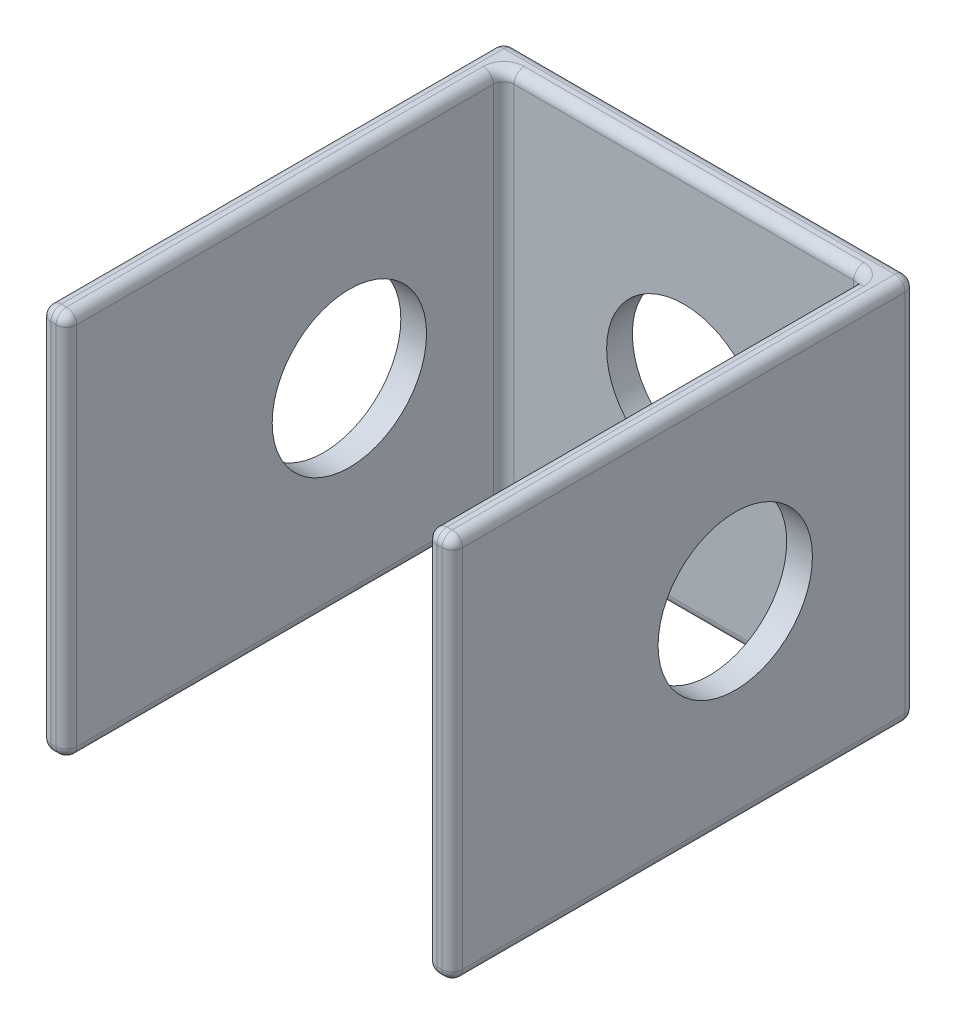
SolidWorks part; units mm, degrees
ref_plane "Front Plane" through (0, 0, 0) normal (0, 0, 1) x (1, 0, 0)
ref_plane "Top Plane" through (0, 0, 0) normal (0, 1, 0) x (1, 0, 0)
ref_plane "Right Plane" through (0, 0, 0) normal (1, 0, 0) x (0, 0, -1)
sketch "Sketch1" plane through (0, 0, 0) normal (0, 1, 0) x (1, 0, 0)
  line L1 (0, 0) -> (80, 0)
  line L2 (0, 0) -> (0, 90)
  line L3 (0, 90) -> (80, 90)
  line L4 (80, 0) -> (80, 90)
  dimension "D1" = 90
  dimension "D2" = 80
extrude "Boss-Extrude1" add sketch "Sketch1" along normal blind 75
sketch "Sketch2" plane through (0, 75, 0) normal (0, 1, 0) x (1, 0, 0)
  line L0 (5, 0) -> (5, 90) construction
  line L1 (0, 0) -> (80, 0) construction
  line L2 (80, 90) -> (0, 90) construction
  line L3 (0, 90) -> (0, 0) construction
  line L4 (75, 90) -> (75, 0) construction
  line L5 (80, 0) -> (80, 90) construction
  line L6 (5, 85) -> (75, 85) construction
  line L7 (5, 0) -> (5, 85)
  line L8 (5, 85) -> (75, 85)
  line L9 (75, 85) -> (75, 0)
  line L10 (5, 0) -> (75, 0)
  dimension "D1" = 5
  dimension "D2" = 5
  dimension "D3" = 5
extrude "Cut-Extrude2" cut sketch "Sketch2" against normal through all
sketch "Sketch3" plane through (0, 0, 0) normal (-1, 0, 0) x (0, 0, 1)
  line L0 (-90, 37.5) -> (0, 37.5) construction
  line L1 (-90, 75) -> (-90, 0) construction
  line L2 (0, 75) -> (0, 0) construction
  line L3 (-70, 10.8781) -> (-70, 53.0416) construction
  circle A0 centre (-55, 37.5) radius 15
  dimension "D1" = 30
  dimension "D2" = 20
extrude "Cut-Extrude3" cut sketch "Sketch3" against normal through all
sketch "Sketch4" plane through (0, 0, -85) normal (0, 0, 1) x (1, 0, 0)
  line L0 (5, 75) -> (75, 0) construction
  circle A0 centre (40, 37.5) radius 15
  dimension "D1" = 30
extrude "Cut-Extrude4" cut sketch "Sketch4" against normal through all
fillet "Fillet1" radius 2 24 edges at (80, 37.5, 0) (77.5, 0, 0) (75, 37.5, 0) (77.5, 75, 0) (0, 37.5, 0) (2.5, 75, 0) (5, 37.5, 0) (2.5, 0, 0) (40, 0, -85) (75, 0, -42.5) (80, 0, -45) (40, 0, -90) (0, 0, -45) (5, 0, -42.5) (0, 75, -45) (40, 75, -90) (80, 75, -45) (75, 75, -42.5) (40, 75, -85) (5, 75, -42.5) (80, 37.5, -90) (0, 37.5, -90) (75, 37.5, -85) (5, 37.5, -85)
